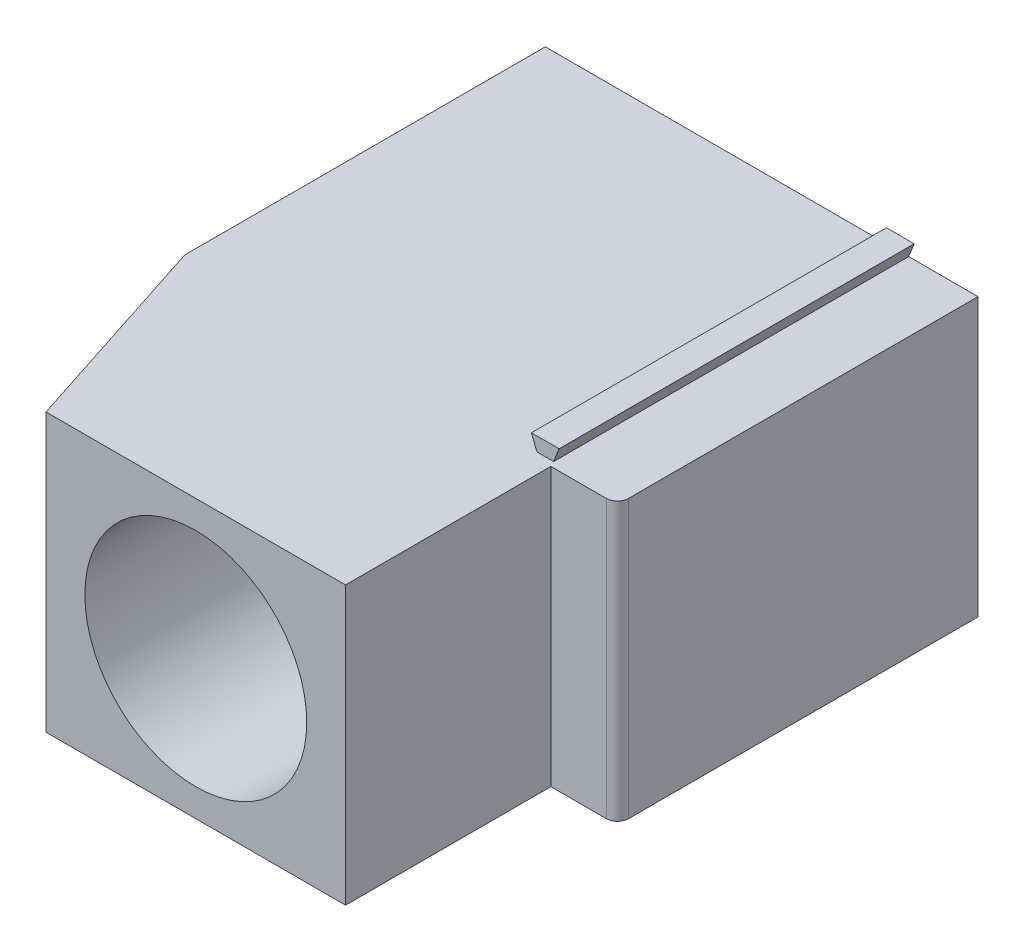
SolidWorks part; units mm, degrees
ref_plane "Спереди" through (0, 0, 0) normal (0, 0, 1) x (1, 0, 0)
ref_plane "Сверху" through (0, 0, 0) normal (0, 1, 0) x (1, 0, 0)
ref_plane "Справа" through (0, 0, 0) normal (1, 0, 0) x (0, 0, -1)
ref_plane "Плоскость1" through (0, 5, 0) normal (0, 1, 0) x (1, 0, 0)
sketch "Эскиз1" plane through (0, 5, 0) normal (0, 1, 0) x (1, 0, 0)
  line L0 (-7.8, -10.2) -> (0, -10.2)
  line L1 (0, -10.2) -> (0, 0)
  line L2 (0, 0) -> (-7.8, 0)
  line L3 (-7.8, 0) -> (-7.8, -10.2)
extrude "Бобышка-Вытянуть1" add sketch "Эскиз1" against normal blind 4.5
sketch "Эскиз2" plane through (0, 0.5, 0) normal (0, -1, 0) x (1, 0, 0)
  line L0 (-6.8, 0.8) -> (-6.8, 5.3)
  line L1 (-6.8, 5.3) -> (-7.8, 6.3)
  line L2 (-7.8, 6.3) -> (-7.8, 0.8)
  line L3 (-7.8, 0.8) -> (-6.8, 0.8)
extrude "Вырез-Вытянуть1" cut sketch "Эскиз2" against normal blind 4
sketch "Эскиз3" plane through (-6.8, 0, 0) normal (-1, 0, 0) x (0, 0, 1)
  line L0 (5.3, 0.5) -> (5.3, 4.5)
  line L1 (5.3, 4.5) -> (0.8, 4.5)
  line L2 (0.8, 4.5) -> (0.8, 0.5)
  line L3 (0.8, 0.5) -> (5.3, 0.5)
extrude "Вырез-Вытянуть2" cut sketch "Эскиз3" against normal blind 4.3
sketch "Эскиз4" plane through (0, 0.5, 0) normal (0, -1, 0) x (1, 0, 0)
  line L0 (0, 10.2) -> (0, 0)
  line L1 (0, 0) -> (-7.8, 0)
  line L2 (-7.8, 0) -> (-7.8, 10.2)
  line L3 (-7.8, 10.2) -> (0, 10.2)
extrude "Бобышка-Вытянуть2" add sketch "Эскиз4" along normal blind 0.5
sketch "Эскиз5" plane through (0, 5, 0) normal (0, 1, 0) x (-1, 0, 0)
  line L0 (0, 6.5) -> (1.2, 6.5)
  line L1 (1.2, 6.5) -> (1.2, 10.2)
  line L2 (1.2, 10.2) -> (0, 10.2)
  line L3 (0, 10.2) -> (0, 6.5)
extrude "Вырез-Вытянуть3" cut sketch "Эскиз5" against normal through all
sketch "Эскиз6" plane through (0, 0, 0) normal (0, 0, -1) x (-1, 0, 0)
  line L0 (7.8, 2.1) -> (7.8, 2.9)
  line L1 (7.8, 2.9) -> (3.7182, 2.9)
  line L2 (3.7182, 2.1) -> (7.8, 2.1)
  line L3 (7.8, 0) -> (7.8, 5) construction
  arc A0 (3.7182, 2.9) -> (3.7182, 2.1) centre (3.7182, 2.5) ccw
  dimension "D2" = 0.4
  dimension "D1" = 4.0818
extrude "Вырез-Вытянуть4" cut sketch "Эскиз6" against normal up to next
sketch "Эскиз7" plane through (0, 5, 0) normal (0, 1, 0) x (-1, 0, 0)
  line L0 (1.55, 0) -> (1.25, 0)
  line L1 (1.25, 0) -> (1.25, 6.4)
  line L2 (1.25, 6.4) -> (1.55, 6.4)
  line L3 (1.55, 6.4) -> (1.55, 0)
extrude "Бобышка-Вытянуть3" add sketch "Эскиз7" along normal blind 0.25
draft "Уклон1" type of draft neutral plane draft angle 21.801 faces to draft 2 face at (-1.55, 5.1562, 2.4) face at (-1.25, 5.1562, 4) neutral plane through (0, 5, 0) neutral plane normal (0, 1, 0) reverse direction yes parameters "D1"=21.801
hole_wizard "Диаметр отверстия Ø4.0 (4)1" positions "Эскиз9" profile "Эскиз8" hole size "Ø4.0" standard "Ansi Metric"
sketch "Эскиз9" plane through (0, 0, 10.2) normal (0, 0, 1) x (1, 0, 0)
  point P0 (-3.9, 2.5)
sketch "Эскиз8" plane through (-3.9, 2.5, 10.2) normal (1, 0, 0) x (0, -1, 0)
  line L0 (0, 0) -> (0, 5.7)
  line L1 (0, 5.7) -> (2, 5.7)
  line L2 (2, 5.7) -> (2, 0)
  line L5 (2, 0) -> (0, 0)
  line L10 (0, 5.7) -> (-2, 5.7) construction
  line L11 (0, -6.35) -> (0, 107.95) construction
  dimension "Диаметр отверстия" = 4
  dimension "Глубина отверстия" = 5.7
  dimension "Угол заточки сверла" = 180
chamfer "Фаска1" distance 1.2 angle 72.031 1 edges at (-7.8, 2.5, 10.2)
fillet "Скругление1" radius 0.2 1 edges at (0, 2.5, 6.5)
